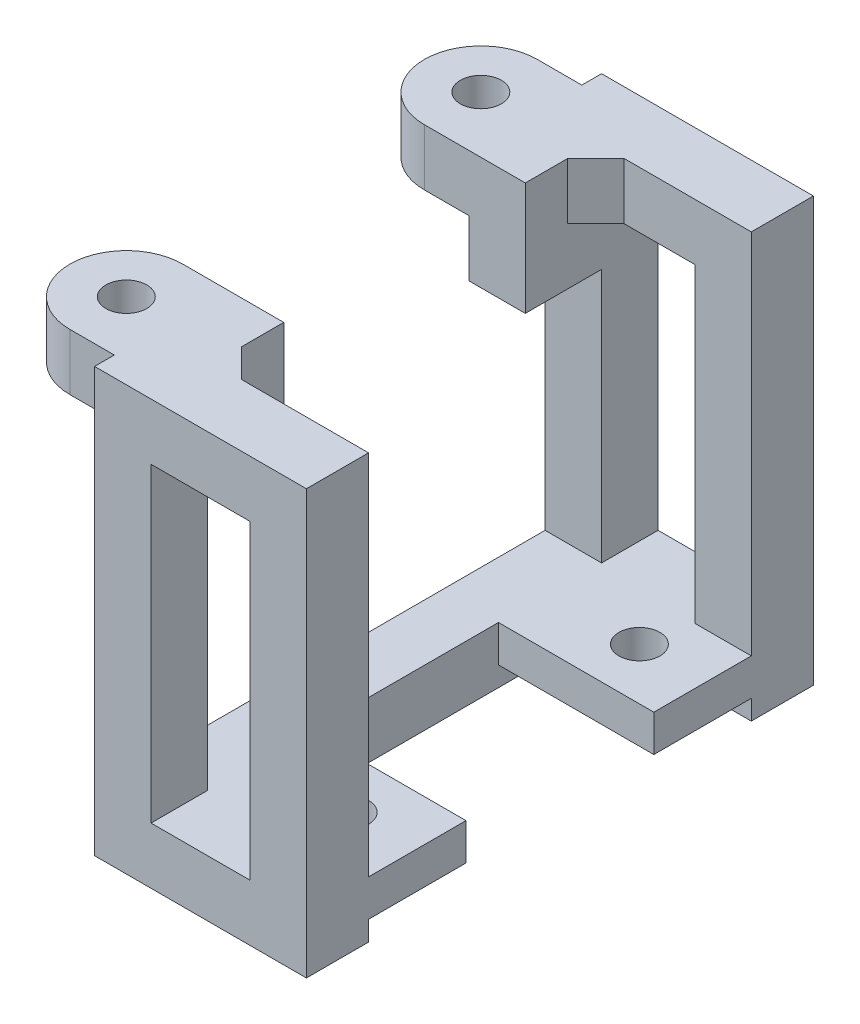
SolidWorks part; units mm, degrees
ref_plane "Front Plane" through (0, 0, 0) normal (0, 0, 1) x (1, 0, 0)
ref_plane "Top Plane" through (0, 0, 0) normal (0, 1, 0) x (1, 0, 0)
ref_plane "Right Plane" through (0, 0, 0) normal (1, 0, 0) x (0, 0, -1)
sketch "Sketch1" plane through (0, 0, 0) normal (0, 1, 0) x (1, 0, 0)
  line L0 (0, 0) -> (0, 13.7135)
  line L1 (0, 13.7135) -> (5.08, 13.7135)
  line L2 (5.08, 13.7135) -> (5.08, 5.588)
  line L3 (5.08, 5.588) -> (19.05, 5.588)
  line L4 (19.05, 5.588) -> (19.05, 0)
  line L5 (19.05, 0) -> (0, 0)
  line L6 (0, 31.8745) -> (5.08, 31.8745)
  line L7 (5.08, 31.8745) -> (5.08, 40.0025)
  line L8 (5.08, 40.0025) -> (19.05, 40.0025)
  line L9 (19.05, 40.0025) -> (19.05, 45.5905)
  line L10 (19.05, 45.5905) -> (0, 45.5905)
  line L11 (0, 45.5905) -> (0, 31.8745)
  dimension "D1" = 19.05
  dimension "D2" = 5.588
  dimension "D3" = 13.7135
  dimension "D4" = 5.08
  dimension "D5" = 5.08
  dimension "D6" = 19.05
  dimension "D7" = 5.588
  dimension "D8" = 13.716
  dimension "D9" = 18.161
extrude "Boss-Extrude1" add sketch "Sketch1" along normal blind 38.1
sketch "Sketch2" plane through (0, 0, 0) normal (-1, 0, 0) x (0, 0, 1)
  line L1 (-10.6655, 38.1) -> (-3.0455, 38.1)
  line L2 (-10.6655, 38.1) -> (-10.6655, 33.02)
  line L3 (-10.6655, 33.02) -> (-3.0455, 33.02)
  line L4 (-3.0455, 38.1) -> (-3.0455, 33.02)
  line L6 (-34.9225, 38.1) -> (-42.5425, 38.1)
  line L7 (-34.9225, 38.1) -> (-34.9225, 33.02)
  line L8 (-34.9225, 33.02) -> (-42.5425, 33.02)
  line L9 (-42.5425, 38.1) -> (-42.5425, 33.02)
  line L10 (-13.7135, 38.1) -> (-13.7135, 0) construction
  line L13 (-31.8745, 38.1) -> (-31.8745, 0) construction
  dimension "D1" = 5.08
  dimension "D2" = 5.08
  dimension "D3" = 7.62
  dimension "D4" = 7.62
  dimension "D5" = 3.048
  dimension "D6" = 3.048
extrude "Boss-Extrude2" add sketch "Sketch2" along normal blind 7.62
sketch "Sketch3" plane through (0, 33.02, 0) normal (0, -1, 0) x (-1, 0, 0)
  line L1 (7.62, 10.6655) -> (0, 10.6655) construction
  line L3 (7.62, 42.5425) -> (0, 42.5425) construction
  circle A0 centre (3.9965, 6.8555) radius 1.8415
  circle A1 centre (3.9965, 38.7325) radius 1.8415
  dimension "D1" = 3.683
  dimension "D4" = 3.683
  dimension "D2" = 3.81
  dimension "D3" = 3.81
extrude "Cut-Extrude1" cut sketch "Sketch3" against normal through all contours A1 | A0
fillet "Fillet1" radius 2.54 2 edges at (-7.62, 35.56, -3.0455) (-7.62, 35.56, -10.6655)
fillet "Fillet2" radius 2.54 2 edges at (-7.62, 35.56, -34.9225) (-7.62, 35.56, -42.5425)
sketch "Sketch5" plane through (0, 0, 0) normal (-1, 0, 0) x (0, 0, 1)
  line L0 (-13.7135, 38.1) -> (-13.7135, 0) construction
  line L1 (-13.7135, 0) -> (-31.8745, 0)
  line L2 (-13.7135, 0) -> (-13.7135, 5.08)
  line L3 (-13.7135, 5.08) -> (-31.8745, 5.08)
  line L4 (-31.8745, 0) -> (-31.8745, 5.08)
  line L5 (-13.7135, 0) -> (0, 0) construction
  line L6 (-31.8745, 38.1) -> (-31.8745, 0) construction
  line L12 (-34.9225, 33.02) -> (-13.7135, 33.02)
  line L13 (-34.9225, 33.02) -> (-34.9225, 27.94)
  line L14 (-34.9225, 27.94) -> (-13.7135, 27.94)
  line L15 (-13.7135, 33.02) -> (-13.7135, 27.94)
  dimension "D1" = 5.08
  dimension "D2" = 5.08
extrude "Boss-Extrude3" add sketch "Sketch5" against normal up to surface (5.08 mm away) up to face at (5.08, 19.05, -35.9385)
sketch "Sketch6" plane through (0, 0, 0) normal (0, 0, 1) x (1, 0, 0)
  line L0 (19.05, 38.1) -> (0, 38.1) construction
  line L10 (13.97, 33.02) -> (5.08, 33.02)
  line L13 (13.97, 33.02) -> (13.97, 5.08)
  line L14 (13.97, 5.08) -> (5.08, 5.08)
  line L15 (5.08, 33.02) -> (5.08, 5.08)
  line L16 (19.05, 38.1) -> (19.05, 0) construction
  line L17 (0, 38.1) -> (0, 0) construction
  line L18 (19.05, 0) -> (0, 0) construction
  dimension "D1" = 5.08
  dimension "D2" = 5.08
  dimension "D3" = 5.08
  dimension "D4" = 5.08
extrude "Cut-Extrude2" cut sketch "Sketch6" against normal through all
sketch "Sketch8" plane through (5.08, 0, 0) normal (1, 0, 0) x (0, 0, -1)
  line L1 (5.588, 5.08) -> (14.351, 5.08)
  line L2 (5.588, 5.08) -> (5.588, 1.778)
  line L3 (5.588, 1.778) -> (14.351, 1.778)
  line L4 (14.351, 5.08) -> (14.351, 1.778)
  line L5 (0, 38.1) -> (0, 0) construction
  line L6 (45.5905, 38.1) -> (45.5905, 0) construction
  line L7 (40.0025, 5.08) -> (31.2395, 5.08)
  line L8 (40.0025, 5.08) -> (40.0025, 1.778)
  line L9 (40.0025, 1.778) -> (31.2395, 1.778)
  line L10 (31.2395, 5.08) -> (31.2395, 1.778)
  dimension "D1" = 14.351
  dimension "D2" = 14.351
  dimension "D3" = 3.302
  dimension "D4" = 3.302
extrude "Boss-Extrude4" add sketch "Sketch8" along normal up to surface (13.97 mm away) up to face at (19.05, 19.05, -42.7965)
sketch "Sketch11" plane through (0, 1.778, 0) normal (0, -1, 0) x (1, 0, 0)
  line L0 (0, 0) -> (19.05, 0) construction
  line L1 (19.05, -45.5905) -> (0, -45.5905) construction
  line L2 (0, -45.5905) -> (0, 0) construction
  circle A0 centre (13.1064, -9.7028) radius 1.8415
  circle A1 centre (13.1064, -35.8877) radius 1.8415
  dimension "D3" = 3.683
  dimension "D4" = 3.683
  dimension "D1" = 9.7028
  dimension "D2" = 9.7028
  dimension "D5" = 13.1064
  dimension "D6" = 13.1064
extrude "Cut-Extrude4" cut sketch "Sketch11" along direction (0, 1, 0) on the side against the normal through all
sketch "Sketch15" plane through (0, 0, 0) normal (-1, 0, 0) x (0, 0, 1)
  line L0 (-5.08, 5.08) -> (-40.5105, 5.08)
  line L2 (-5.08, 27.94) -> (-40.5105, 27.94)
  line L4 (-45.5905, 38.1) -> (-45.5905, 0) construction
  line L5 (0, 38.1) -> (0, 0) construction
  line L6 (-5.08, 5.08) -> (-5.08, 27.94)
  line L7 (-40.5105, 5.08) -> (-40.5105, 27.94)
  point P3 (-22.7952, 5.08)
  point P6 (-22.7952, 27.94)
  dimension "D1" = 5.08
  dimension "D2" = 5.08
  dimension "D3" = 5.08
  dimension "D4" = 5.08
extrude "Cut-Extrude5" cut sketch "Sketch15" against normal up to next and the other way through all
sketch "Sketch16" plane through (0, 38.1, 0) normal (0, 1, 0) x (1, 0, 0)
  line L0 (-3.9965, 38.7325) -> (3.1077, 38.7325) construction
  line L1 (-3.9965, 43.8125) -> (3.1077, 43.8125)
  line L2 (-3.9965, 33.6525) -> (3.0425, 33.6525)
  line L3 (-3.9965, 6.8555) -> (2.838, 6.8555) construction
  line L4 (-3.9965, 11.9355) -> (2.838, 11.9355)
  line L5 (-3.9965, 1.7755) -> (2.838, 1.7755)
  line L6 (3.1077, 43.8125) -> (3.0425, 33.6525)
  line L7 (2.9032, 11.935) -> (2.838, 1.7755)
  arc A0 (-3.9965, 43.8125) -> (-3.9965, 33.6525) centre (-3.9965, 38.7325) ccw
  arc A2 (-3.9965, 11.9355) -> (-3.9965, 1.7755) centre (-3.9965, 6.8555) ccw
  arc A3 (2.9032, 11.935) -> (2.838, 11.9355) centre (2.838, 6.8555) ccw
  circle A4 centre (-3.9965, 38.7325) radius 1.8415
  circle A5 centre (-3.9965, 6.8555) radius 1.8415
  point P3 (-0.4444, 38.7325)
  point P8 (-0.5793, 6.8555)
  dimension "D1" = 5.08
  dimension "D2" = 5.08
extrude "Boss-Extrude5" add sketch "Sketch16" against normal up to surface (5.08 mm away) up to face at (-3.9965, 33.02, -40.574)
sketch "Sketch17" plane through (0, 38.1, 0) normal (0, 1, 0) x (1, 0, 0)
  line L0 (5.08, 5.588) -> (5.08, 13.7135) construction
  line L1 (0, 33.6525) -> (5.08, 33.6525)
  line L2 (0, 33.6525) -> (0, 11.9355)
  line L3 (0, 11.9355) -> (5.08, 11.9355)
  line L4 (5.08, 33.6525) -> (5.08, 11.9355)
extrude "Cut-Extrude6" cut sketch "Sketch17" against normal up to surface (10.16 mm away) up to face at (2.54, 27.94, -22.7952)
chamfer "Chamfer1" distance 2.54 angle 45 2 edges at (5.08, 35.56, -40.0025) (5.08, 35.56, -5.588)
